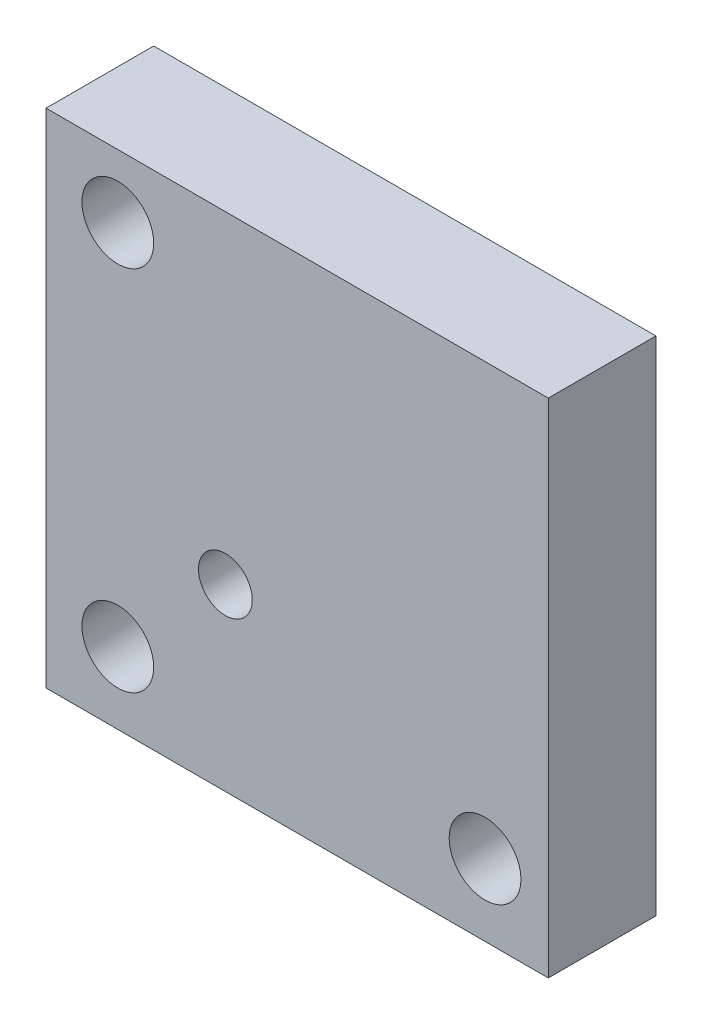
SolidWorks part; units mm, degrees
material "3D Printer - Undefined Plastic"
ref_plane "Front Plane" through (0, 0, 0) normal (0, 0, 1) x (1, 0, 0)
ref_plane "Top Plane" through (0, 0, 0) normal (0, 1, 0) x (1, 0, 0)
ref_plane "Right Plane" through (0, 0, 0) normal (1, 0, 0) x (0, 0, -1)
sketch "Sketch1" plane through (0, 0, 0) normal (0, 0, 1) x (1, 0, 0)
  line L1 (-22.225, -22.225) -> (22.225, -22.225)
  line L2 (-22.225, -22.225) -> (-22.225, 22.225)
  line L3 (-22.225, 22.225) -> (22.225, 22.225)
  line L4 (22.225, -22.225) -> (22.225, 22.225)
  line L5 (-22.225, -22.225) -> (22.225, 22.225) construction
  line L6 (-22.225, 22.225) -> (22.225, -22.225) construction
  point P0 (0, 0)
  dimension "D1" = 44.45
  dimension "D2" = 44.45
extrude "Boss-Extrude1" add sketch "Sketch1" along normal blind 9.525
hole_wizard "CBORE for 1/4 _1" positions "Sketch4" profile "Sketch5" counterbore size "1/4" standard "ANSI Inch" end condition up to next
sketch "Sketch4" plane through (0, 0, 0) normal (0, 0, -1) x (-1, 0, 0)
  line L0 (15.875, 16.6261) -> (15.875, -15.875) construction
  line L2 (15.875, -15.875) -> (-16.6261, -15.875) construction
  line L4 (22.225, -22.225) -> (-22.225, -22.225) construction
  line L5 (22.225, 22.225) -> (22.225, -22.225) construction
  point P0 (15.875, 16.6261)
  point P2 (-16.6261, -15.875)
  point P4 (15.875, -15.875)
  dimension "D1" = 6.35
  dimension "D2" = 6.35
sketch "Sketch5" plane through (-15.875, 16.6261, 0) normal (1, 0, 0) x (0, 1, 0)
  line L0 (0, 0) -> (0, 9.525)
  line L1 (0, 9.525) -> (3.175, 9.525)
  line L3 (3.175, 9.525) -> (3.175, 0.508)
  line L4 (3.81, 0.508) -> (3.175, 0.508)
  line L5 (3.81, 0.508) -> (3.81, 0.127)
  line L6 (3.81, 0.127) -> (3.937, 0)
  line L7 (3.937, 0) -> (0, 0)
  line L8 (-3.81, 0.127) -> (-3.937, 0) construction
  line L11 (0, -6.35) -> (0, 107.95) construction
  dimension "Thru Hole Dia." = 6.35
  dimension "Thru Hole Depth" = 9.525
  dimension "C'Bore Dia." = 7.62
  dimension "C'Bore Depth" = 0.508
  dimension "Near C'Sink Dia." = 7.874
  dimension "Near C'Sink Angle" = 90
sketch "Sketch6" plane through (0, 0, 0) normal (0, 0, -1) x (-1, 0, 0)
  circle A0 centre (6.3557, -6.3557) radius 6.35
  point P2 (6.3557, -6.3557)
  dimension "D1" = 12.7
extrude "Cut-Extrude1" cut sketch "Sketch6" against normal blind 4.7752
sketch "Sketch7" plane through (0, 0, 0) normal (0, 0, -1) x (-1, 0, 0)
  circle A0 centre (6.3557, -6.3557) radius 2.3813
  circle A1 centre (6.3557, -6.3557) radius 6.35 construction
  dimension "D1" = 4.7625
extrude "Cut-Extrude2" cut sketch "Sketch7" against normal through all
